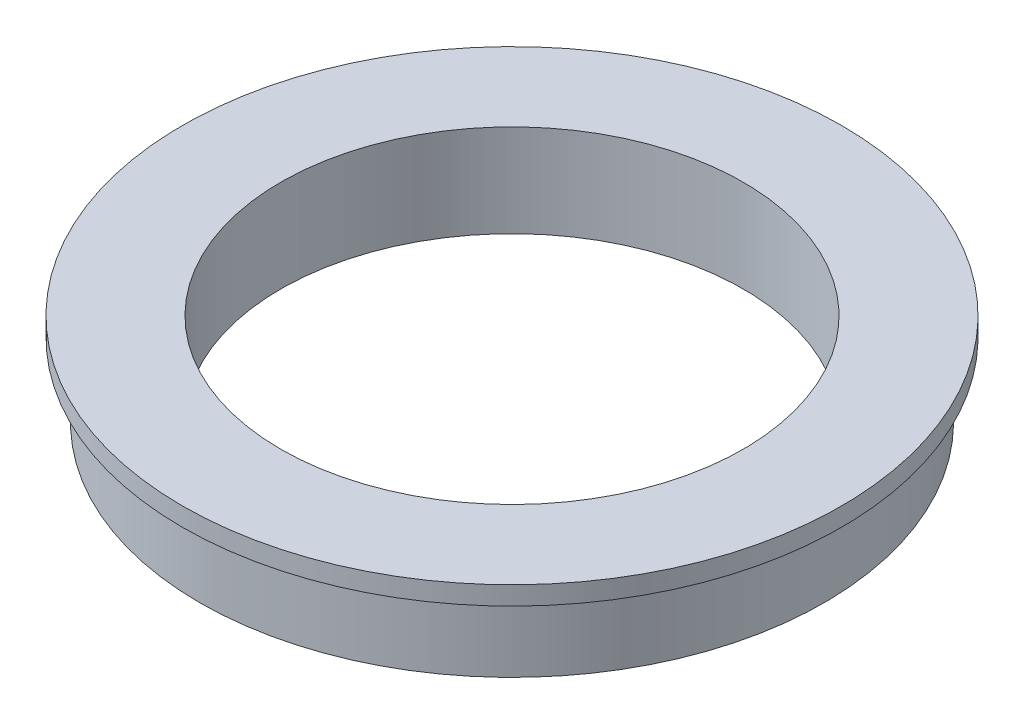
SolidWorks part; units mm, degrees
material "铸造不锈钢"
ref_plane "前视基准面" through (0, 0, 0) normal (0, 0, 1) x (1, 0, 0)
ref_plane "上视基准面" through (0, 0, 0) normal (0, 1, 0) x (1, 0, 0)
ref_plane "右视基准面" through (0, 0, 0) normal (1, 0, 0) x (0, 0, -1)
other "Configuration Table"
sketch "草图1" plane through (0, 0, 0) normal (0, 1, 0) x (1, 0, 0)
  circle A0 centre (0, 0) radius 10
  circle A1 centre (0, 0) radius 13.5
  dimension "D1" = 20
  dimension "D2" = 27
extrude "凸台-拉伸1" add sketch "草图1" along normal blind 3.2
sketch "草图2" plane through (0, 3.2, 0) normal (0, 1, 0) x (1, 0, 0)
  circle A0 centre (0, 0) radius 10
  circle A1 centre (0, 0) radius 14.25
  dimension "D1" = 28.5
  dimension "D2" = 20
extrude "凸台-拉伸2" add sketch "草图2" along normal blind 0.8
